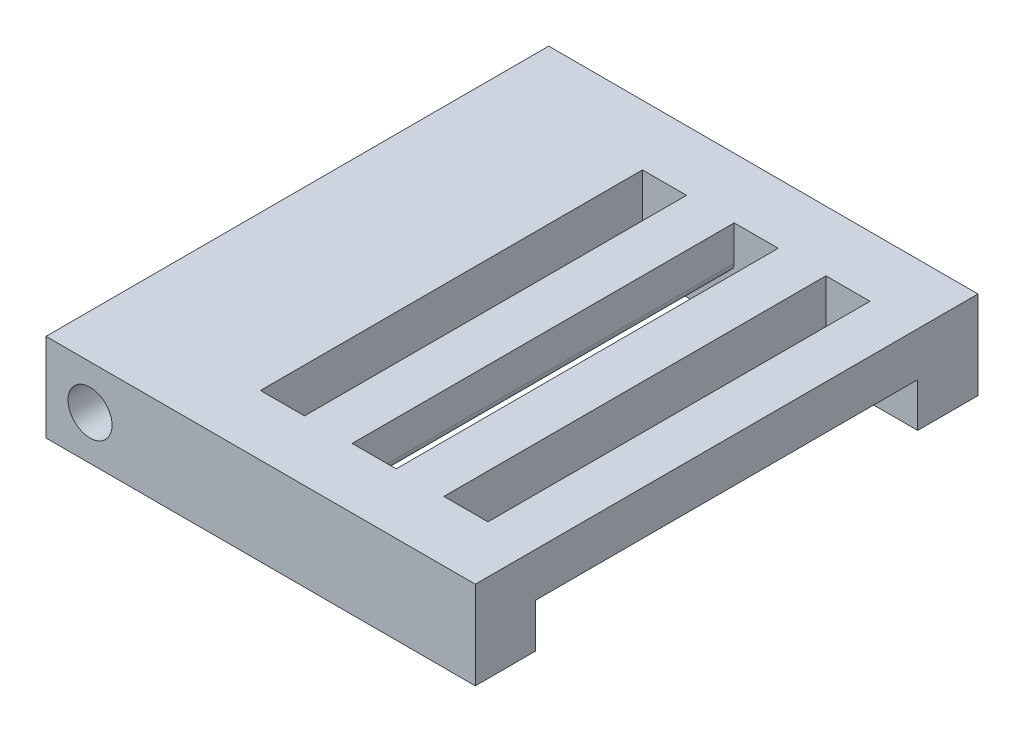
SolidWorks part; units mm, degrees
ref_plane "Plan de face" through (0, 0, 0) normal (0, 0, 1) x (1, 0, 0)
ref_plane "Plan de dessus" through (0, 0, 0) normal (0, 1, 0) x (1, 0, 0)
ref_plane "Plan de droite" through (0, 0, 0) normal (1, 0, 0) x (0, 0, -1)
sketch "Esquisse1" plane through (0, 0, 0) normal (0, 1, 0) x (1, 0, 0)
  line L0 (-82.5, 77.5) -> (-72.5, 77.5)
  line L1 (82.5, 82.5) -> (-82.5, 82.5)
  line L2 (82.5, 82.5) -> (82.5, 77.5)
  line L3 (82.5, -82.5) -> (-82.5, -82.5)
  line L4 (-82.5, 82.5) -> (-82.5, 77.5)
  line L5 (82.5, 82.5) -> (-82.5, -82.5) construction
  line L6 (82.5, -82.5) -> (-82.5, 82.5) construction
  line L7 (-72.5, 77.5) -> (-72.5, 67.5)
  line L8 (-72.5, 67.5) -> (-82.5, 67.5)
  line L9 (-82.5, -2.5) -> (-72.5, -2.5)
  line L10 (-72.5, -2.5) -> (-72.5, -12.5)
  line L11 (-72.5, -12.5) -> (-82.5, -12.5)
  line L12 (-82.5, -2.5) -> (-72.5, -12.5) construction
  line L13 (-72.5, -12.5) -> (-72.5448, -12.5817) construction
  line L14 (-82.5, 67.5) -> (-82.5, -2.5)
  line L15 (-82.5, -12.5) -> (-82.5, -82.5)
  line L16 (0, 16.0212) -> (0, -17.3175) construction
  line L17 (72.5, -12.5) -> (82.5, -12.5)
  line L18 (72.5, -2.5) -> (72.5, -12.5)
  line L19 (82.5, -2.5) -> (72.5, -2.5)
  line L20 (72.5, 77.5) -> (72.5, 67.5)
  line L21 (82.5, 77.5) -> (72.5, 77.5)
  line L22 (72.5, 67.5) -> (82.5, 67.5)
  line L23 (82.5, 67.5) -> (82.5, -2.5)
  line L24 (82.5, -12.5) -> (82.5, -82.5)
  line L25 (60, 74.3519) -> (60, -75.6481)
  line L26 (60, -75.6481) -> (65, -75.6481)
  line L27 (65, 74.3519) -> (65, -75.6481)
  line L28 (65, 74.3519) -> (60, 74.3519)
  line L29 (0, -0.6481) -> (73.9964, -0.6481) construction
  line L30 (49.5833, 74.3519) -> (49.5833, -75.6481)
  line L31 (54.5833, -75.6481) -> (54.5833, 74.3519)
  line L32 (54.5833, 74.3519) -> (49.5833, 74.3519)
  line L33 (49.5833, -75.6481) -> (54.5833, -75.6481)
  line L34 (39.1667, 74.3519) -> (39.1667, -75.6481)
  line L35 (44.1667, -75.6481) -> (44.1667, 74.3519)
  line L36 (44.1667, 74.3519) -> (39.1667, 74.3519)
  line L37 (39.1667, -75.6481) -> (44.1667, -75.6481)
  line L38 (28.75, 74.3519) -> (28.75, -75.6481)
  line L39 (33.75, -75.6481) -> (33.75, 74.3519)
  line L40 (33.75, 74.3519) -> (28.75, 74.3519)
  line L41 (28.75, -75.6481) -> (33.75, -75.6481)
  line L42 (18.3333, 74.3519) -> (18.3333, -75.6481)
  line L43 (23.3333, -75.6481) -> (23.3333, 74.3519)
  line L44 (23.3333, 74.3519) -> (18.3333, 74.3519)
  line L45 (18.3333, -75.6481) -> (23.3333, -75.6481)
  line L46 (7.9167, 74.3519) -> (7.9167, 12.0926)
  line L47 (12.9167, -75.6481) -> (12.9167, -8.2744)
  line L48 (12.9167, 74.3519) -> (7.9167, 74.3519)
  line L49 (7.9167, -75.6481) -> (12.9167, -75.6481)
  line L50 (-2.5, 74.3519) -> (-2.5, 14.1421)
  line L51 (2.5, -75.6481) -> (2.5, -15.4383)
  line L52 (2.5, 74.3519) -> (-2.5, 74.3519)
  line L53 (-2.5, -75.6481) -> (2.5, -75.6481)
  line L54 (-12.9167, 74.3519) -> (-12.9167, 6.9781)
  line L55 (-7.9167, -75.6481) -> (-7.9167, -13.3888)
  line L56 (-7.9167, 74.3519) -> (-12.9167, 74.3519)
  line L57 (-12.9167, -75.6481) -> (-7.9167, -75.6481)
  line L58 (-23.3333, 74.3519) -> (-23.3333, -75.6481)
  line L59 (-18.3333, -75.6481) -> (-18.3333, 74.3519)
  line L60 (-18.3333, 74.3519) -> (-23.3333, 74.3519)
  line L61 (-23.3333, -75.6481) -> (-18.3333, -75.6481)
  line L62 (-33.75, 74.3519) -> (-33.75, -75.6481)
  line L63 (-28.75, -75.6481) -> (-28.75, 74.3519)
  line L64 (-28.75, 74.3519) -> (-33.75, 74.3519)
  line L65 (-33.75, -75.6481) -> (-28.75, -75.6481)
  line L66 (-44.1667, 74.3519) -> (-44.1667, -75.6481)
  line L67 (-39.1667, -75.6481) -> (-39.1667, 74.3519)
  line L68 (-39.1667, 74.3519) -> (-44.1667, 74.3519)
  line L69 (-44.1667, -75.6481) -> (-39.1667, -75.6481)
  line L70 (-54.5833, 74.3519) -> (-54.5833, -75.6481)
  line L71 (-49.5833, -75.6481) -> (-49.5833, 74.3519)
  line L72 (-49.5833, 74.3519) -> (-54.5833, 74.3519)
  line L73 (-54.5833, -75.6481) -> (-49.5833, -75.6481)
  line L74 (-65, 74.3519) -> (-65, -75.6481)
  line L75 (-60, -75.6481) -> (-60, 74.3519)
  line L76 (-60, 74.3519) -> (-65, 74.3519)
  line L77 (-65, -75.6481) -> (-60, -75.6481)
  line L78 (12.9167, 6.9781) -> (12.9167, 74.3519)
  line L79 (7.9167, -13.3888) -> (7.9167, -75.6481)
  line L80 (2.5, 14.1421) -> (2.5, 74.3519)
  line L81 (-12.9167, -8.2744) -> (-12.9167, -75.6481)
  line L82 (-7.9167, 12.0926) -> (-7.9167, 74.3519)
  line L83 (-2.5, -15.4383) -> (-2.5, -75.6481)
  circle A0 centre (0, -0.6481) radius 15
  circle A1 centre (0, -0.6481) radius 16.5
  point P0 (0, 0)
  point P12 (-77.5, -7.5)
  point P32 (60, -0.6481)
  dimension "D9" = 30
  dimension "D15" = 1.5
  dimension "D1" = 165
  dimension "D2" = 165
  dimension "D3" = 5
  dimension "D4" = 10
  dimension "D5" = 10
  dimension "D6" = 10
  dimension "D7" = 10
  dimension "D8" = 90
  dimension "D10" = 5
  dimension "D11" = 150
  dimension "D12" = 60
  dimension "D14" = 65
  dimension "D13" = 13
extrude "BASE" add sketch "Esquisse1" along normal blind 10 contours L24 L17 L18 L19 L23 L22 L20 L21 L2 L1 L4 L0 L7 L8 L14 L9 L10 L11 L15 L3 A0 L51 L53 L83 L55 L57 L81 L54 L56 L82 L50 L52 L80 L46 L48 L78 L47 L49 L79 L77 L74 L76 L75 | L54 A1 L81 A0
sketch "Esquisse5" plane through (0, 0, 12.5) normal (0, 0, -1) x (-1, 0, 0)
  line L0 (-82.5, 10) -> (-72.5, 0) construction
  line L1 (-82.5, 0) -> (82.5, 0) construction
  line L2 (-72.5, 0) -> (-72.5, 10) construction
  line L3 (-82.5, 10) -> (82.5, 10) construction
  line L4 (-72.5, 10) -> (-82.5, 0) construction
  line L5 (-82.5, 10) -> (-82.5, 0) construction
  line L6 (0, 13.0138) -> (0, -4.3994) construction
  line L7 (72.5, 10) -> (82.5, 0) construction
  line L8 (72.5, 0) -> (72.5, 10) construction
  line L9 (82.5, 10) -> (72.5, 0) construction
  circle A0 centre (-77.5, 5) radius 2.5
  circle A1 centre (77.5, 5) radius 2.5
  dimension "D2" = 5
  dimension "D1" = 10
extrude "VIDE VIS" cut sketch "Esquisse5" against normal through all both and the other way through all
sketch "Esquisse6" plane through (0, 0, 0) normal (0, -1, 0) x (1, 0, 0)
  line L1 (65, -74.3519) -> (-65, -74.3519)
  line L2 (65, -74.3519) -> (65, 75.6481)
  line L3 (65, 75.6481) -> (-65, 75.6481)
  line L4 (-65, -74.3519) -> (-65, 75.6481)
  line L5 (65, -74.3519) -> (-65, 75.6481) construction
  line L6 (65, 75.6481) -> (-65, -74.3519) construction
  point P0 (0, 0.6481)
extrude "Enlèv. mat.-Extru.6" cut sketch "Esquisse6" against normal blind 5
sketch "Esquisse7" plane through (0, 10, 0) normal (0, 1, 0) x (1, 0, 0)
  line L0 (-33.75, 74.3519) -> (-33.75, -75.6481) construction
  line L1 (-82.5, -82.5) -> (-33.75, -82.5)
  line L2 (-82.5, -82.5) -> (-82.5, -25.4163)
  line L3 (-82.5, -25.4163) -> (-33.75, -25.4163)
  line L4 (-33.75, -82.5) -> (-33.75, -25.4163)
  line L6 (-82.5, -82.5) -> (82.5, -82.5)
  line L7 (-82.5, -82.5) -> (-82.5, 82.5)
  line L8 (-82.5, 82.5) -> (82.5, 82.5)
  line L9 (82.5, -82.5) -> (82.5, 82.5)
extrude "VIDE TEST" cut sketch "Esquisse7" against normal through all contours L6 L9 L8 L7 L3 L4
sketch "Esquisse8" plane through (0, 0, 0) normal (0, -1, 0) x (1, 0, 0)
  line L0 (-65, 25.4163) -> (-33.75, 25.4163)
  line L1 (-33.75, 25.4163) -> (-33.75, 32.2663)
  line L2 (-33.75, 75.6481) -> (-33.75, 25.4163) construction
  line L3 (-33.75, 32.2663) -> (-65, 32.2663)
  line L4 (-65, 25.4163) -> (-65, 75.6481) construction
  line L5 (-65, 32.2663) -> (-65, 25.4163)
  line L6 (-33.75, 75.6481) -> (-65, 75.6481) construction
  line L7 (-65, 75.6481) -> (-65, 82.5) construction
  line L8 (-33.75, 82.5) -> (-82.5, 82.5) construction
  line L9 (-65, 82.5) -> (-33.75, 82.5) construction
  dimension "D1" = 6.85
extrude "BOSS FERME" add sketch "Esquisse8" along direction (0, 1, 0) on the side against the normal up to surface (10 mm away)
fillet "CONGE TEST" radius 1 2 edges at (-54.5833, 5, 53.9572) (-49.5833, 5, 53.9572)
